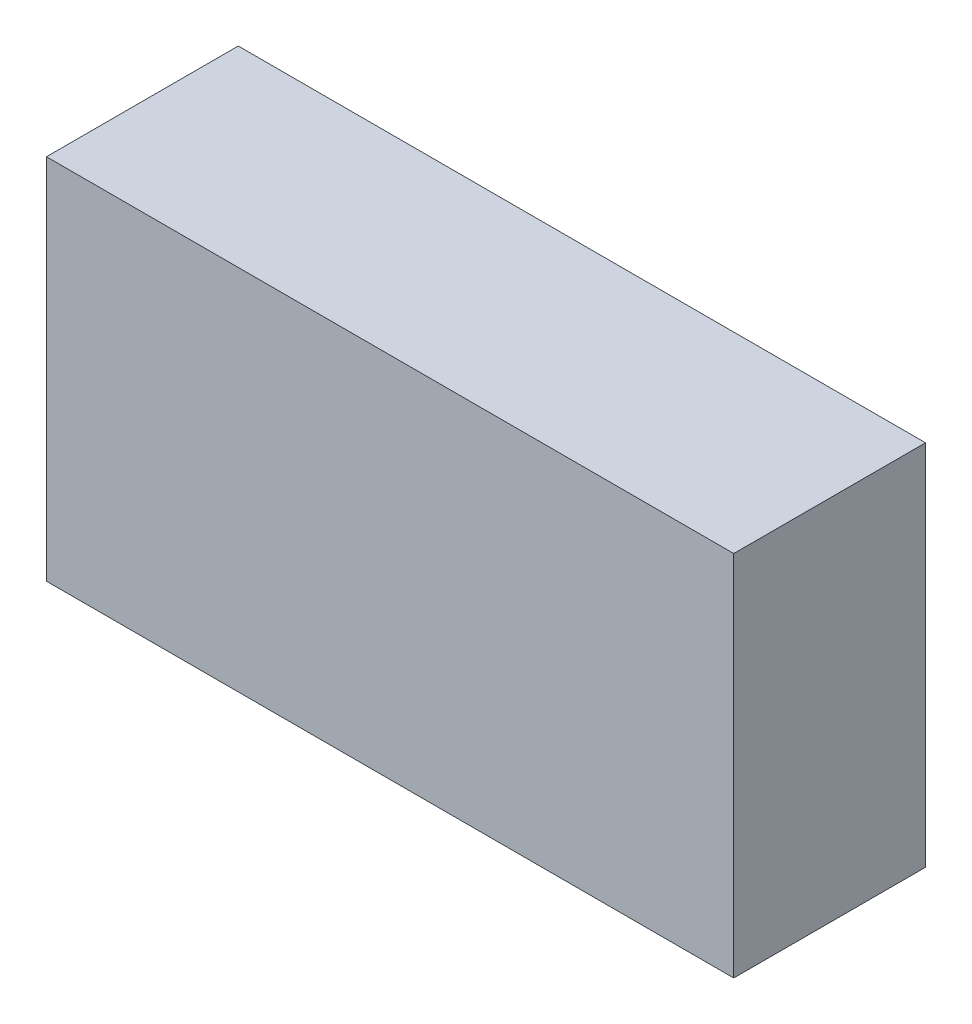
SolidWorks part; units mm, degrees
material "Polyether Polyol"
ref_plane "Front Plane" through (0, 0, 0) normal (0, 0, 1) x (1, 0, 0)
ref_plane "Top Plane" through (0, 0, 0) normal (0, 1, 0) x (1, 0, 0)
ref_plane "Right Plane" through (0, 0, 0) normal (1, 0, 0) x (0, 0, -1)
sketch "Sketch1" plane through (0, 0, 0) normal (0, 0, 1) x (1, 0, 0)
  line L1 (0, 0) -> (54.61, 0)
  line L2 (0, 0) -> (0, 29.21)
  line L3 (0, 29.21) -> (54.61, 29.21)
  line L4 (54.61, 0) -> (54.61, 29.21)
  line L5 (0, 0) -> (54.61, 29.21) construction
  line L6 (0, 29.21) -> (54.61, 0) construction
  point P4 (27.305, 14.605)
  dimension "D1" = 29.21
  dimension "D2" = 54.61
extrude "Boss-Extrude1" add sketch "Sketch1" along normal blind 15.24
